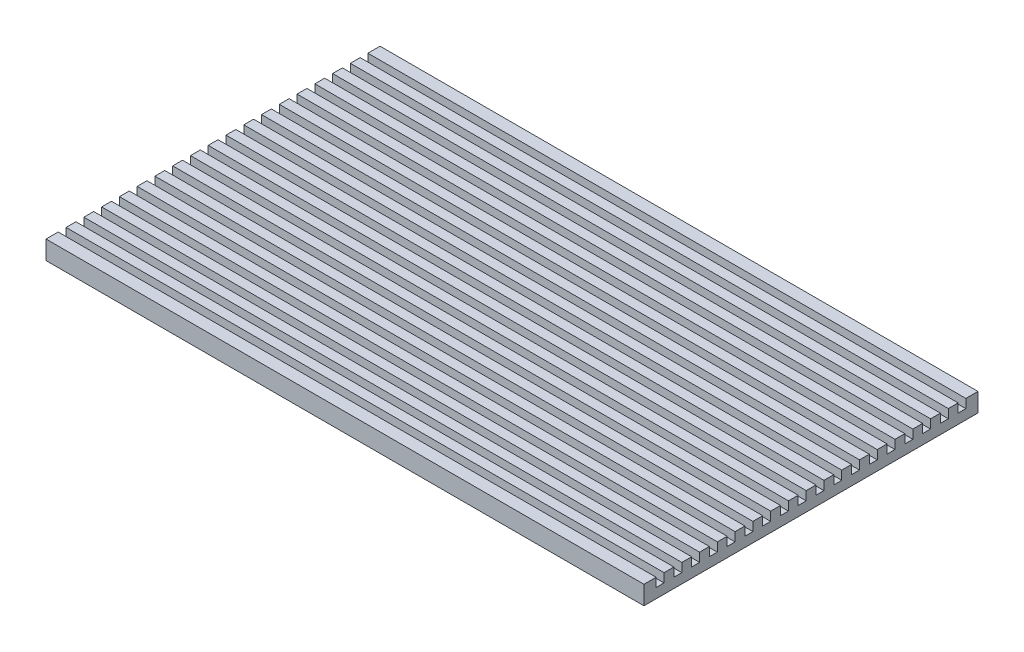
SolidWorks part; units mm, degrees
ref_plane "Front Plane" through (0, 0, 0) normal (0, 0, 1) x (1, 0, 0)
ref_plane "Top Plane" through (0, 0, 0) normal (0, 1, 0) x (1, 0, 0)
ref_plane "Right Plane" through (0, 0, 0) normal (1, 0, 0) x (0, 0, -1)
sketch "Sketch1" plane through (0, 0, 0) normal (0, 1, 0) x (1, 0, 0)
  line L1 (64, 35.75) -> (-64, 35.75)
  line L2 (64, 35.75) -> (64, -35.75)
  line L3 (64, -35.75) -> (-64, -35.75)
  line L4 (-64, 35.75) -> (-64, -35.75)
  line L5 (64, 35.75) -> (-64, -35.75) construction
  line L6 (64, -35.75) -> (-64, 35.75) construction
  point P0 (0, 0)
  dimension "D1" = 71.5
  dimension "D2" = 128
extrude "Boss-Extrude1" add sketch "Sketch1" along normal blind 2.1 and the other way blind 0.0001
sketch "Sketch2" plane through (0, 2.1, 0) normal (0, 1, 0) x (1, 0, 0)
  line L0 (64, -35.75) -> (64, 35.75) construction
  line L1 (-64, -35.75) -> (64, -35.75)
  line L2 (-64, -35.75) -> (-64, -33.15)
  line L3 (-64, -33.15) -> (64, -33.15)
  line L4 (64, -35.75) -> (64, -33.15)
  line L6 (-64, 35.75) -> (64, 35.75)
  line L7 (-64, 35.75) -> (-64, 33.15)
  line L8 (-64, 33.15) -> (64, 33.15)
  line L9 (64, 35.75) -> (64, 33.15)
  dimension "D1" = 2.6
extrude "Boss-Extrude2" add sketch "Sketch2" along normal offset from surface (1.8999 mm away) 4 up to face at (0, -0.0001, 0)
sketch "Sketch3" plane through (0, 2.1, 0) normal (0, 1, 0) x (1, 0, 0)
  line L0 (-64, 33.15) -> (-64, -33.15) construction
  line L1 (-64, -31.45) -> (64, -31.45)
  line L2 (-64, -31.45) -> (-64, -29.35)
  line L3 (-64, -29.35) -> (64, -29.35)
  line L4 (64, -31.45) -> (64, -29.35)
  line L5 (64, -33.15) -> (64, 33.15) construction
  line L6 (-64, -33.15) -> (64, -33.15) construction
  dimension "D1" = 2.1
  dimension "D2" = 1.7
extrude "Boss-Extrude3" add sketch "Sketch3" along normal up to surface (1.8999 mm away) up to face at (0, 3.9999, 34.45)
pattern_linear "LPattern1" count 17 spacing 3.8031 along (0, 0, -1) of "Boss-Extrude3"
sketch "Sketch4" plane through (0, -0.0001, 0) normal (0, -1, 0) x (1, 0, 0)
  line L0 (64, -35.75) -> (-64, -35.75) construction
  line L1 (-64, -35.75) -> (-64, 35.75) construction
  line L2 (0, 0) -> (0, -35.75) construction
  line L5 (-64, 35.75) -> (64, 35.75) construction
  circle A0 centre (-51.4, -31.8) radius 1.2 construction
  circle A1 centre (0, -31.8) radius 1.2 construction
  circle A2 centre (51.4, -31.8) radius 1.2 construction
  circle A3 centre (-51.4, 5.5) radius 1.2 construction
  circle A4 centre (0, 5.5) radius 1.2 construction
  circle A5 centre (51.4, 5.5) radius 1.2 construction
  point P19 (0, 0)
  point P20 (0, 0)
  point P21 (-51.4, 5.5)
  dimension "D1" = 2.4
  dimension "D3" = 11.4
  dimension "D4" = 49
  dimension "D5" = 34.9
  dimension "D6" = 29.05
  dimension "D2" = 2.75
sketch "Sketch5" plane through (0, -0.0001, 0) normal (0, -1, 0) x (1, 0, 0)
  circle A0 centre (-51.4, -31.8) radius 1.6 construction
  circle A1 centre (0, -31.8) radius 1.6 construction
  circle A2 centre (51.4, -31.8) radius 1.6 construction
  circle A3 centre (51.4, 5.5) radius 1.6 construction
  circle A4 centre (0, 5.5) radius 1.6 construction
  circle A5 centre (-51.4, 5.5) radius 1.6 construction
  dimension "D1" = 3.2
  dimension "D2" = 48.2
  dimension "D3" = 34.1
sketch "Sketch6" plane through (0, -0.0001, 0) normal (0, -1, 0) x (1, 0, 0)
  line L0 (0, 5.5) -> (0, -31.8) construction
  line L2 (-52.5, -22.775) -> (52.5, -22.775)
  line L3 (-52.5, -22.775) -> (-52.5, -3.525)
  line L4 (-52.5, -3.525) -> (52.5, -3.525)
  line L5 (52.5, -22.775) -> (52.5, -3.525)
  line L6 (-52.5, -22.775) -> (52.5, -3.525) construction
  line L7 (-52.5, -3.525) -> (52.5, -22.775) construction
  point P4 (0, -13.15)
  dimension "D1" = 19.25
  dimension "D2" = 105
extrude "Boss-Extrude4" add sketch "Sketch6" along normal blind 5.5
